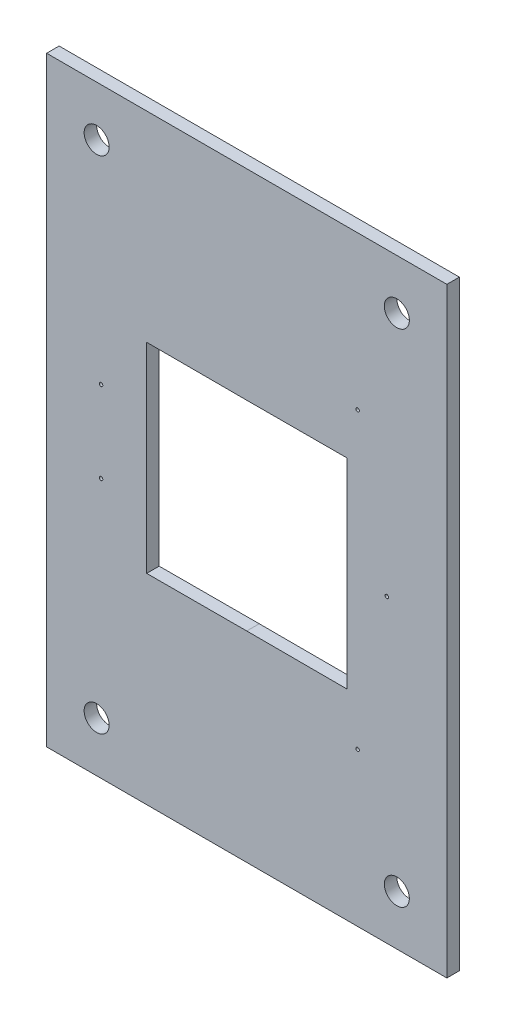
SolidWorks part; units mm, degrees
ref_plane "Front Plane" through (0, 0, 0) normal (0, 0, 1) x (1, 0, 0)
ref_plane "Top Plane" through (0, 0, 0) normal (0, 1, 0) x (1, 0, 0)
ref_plane "Right Plane" through (0, 0, 0) normal (1, 0, 0) x (0, 0, -1)
sketch "Sketch2" plane through (0, 0, 0) normal (0, 0, 1) x (1, 0, 0)
  line L0 (367.9685, -43.1374) -> (375.3903, -43.1374) construction
  line L1 (339.8232, 33.108) -> (339.8232, -119.3829) construction
  line L3 (365.2232, -43.1374) -> (365.2232, -17.7374) construction
  line L4 (365.2232, -17.7374) -> (339.8232, -17.7783)
  line L5 (365.2232, -17.7374) -> (365.2232, -68.5374)
  line L6 (314.4232, -17.7374) -> (339.8232, -17.7783)
  line L7 (314.4232, -17.7374) -> (314.4232, -68.5374)
  line L8 (365.2232, -68.5374) -> (339.8232, -68.4966)
  line L9 (314.4232, -68.5374) -> (339.8232, -68.4966)
  line L10 (390.6232, 33.108) -> (289.0232, 33.108)
  line L11 (289.0232, 33.108) -> (289.0232, -119.3829)
  line L12 (289.0232, -119.3829) -> (390.6232, -119.3829)
  line L13 (390.6232, 33.108) -> (390.6232, -119.3829)
  line L14 (289.0232, -43.1374) -> (302.835, -43.1374) construction
  line L15 (302.835, -43.1374) -> (302.835, -32.805) construction
  line L16 (302.835, -32.805) -> (367.9685, -5.8258) construction
  line L17 (367.9685, -5.8258) -> (367.9685, -43.1374) construction
  line L18 (368.6791, -6.2758) -> (368.6791, -5.8258) construction
  circle A0 centre (302.835, -32.805) radius 0.45
  circle A1 centre (367.9685, -5.8258) radius 0.45
  circle A2 centre (302.835, -53.4699) radius 0.45
  circle A3 centre (375.3903, -43.1374) radius 0.45
  circle A4 centre (367.9685, -80.449) radius 0.45
  point P28 (314.4232, -43.1374)
  dimension "D3" = 25.4
  dimension "D4" = 50.8
  dimension "D5" = 13.8118
extrude "Boss-Extrude1" add sketch "Sketch2" along normal blind 3.175
sketch "Sketch3" plane through (0, 0, 3.175) normal (0, 0, 1) x (1, 0, 0)
  line L0 (339.8232, 33.108) -> (339.8232, -119.3829) construction
  line L1 (390.6232, 33.108) -> (289.0232, 33.108) construction
  line L2 (289.0232, -119.3829) -> (390.6232, -119.3829) construction
  line L3 (289.0232, -43.1374) -> (390.6232, -43.1374) construction
  line L4 (289.0232, 33.108) -> (289.0232, -119.3829) construction
  line L5 (390.6232, -119.3829) -> (390.6232, 33.108) construction
  line L6 (390.6232, 33.108) -> (377.9232, 33.108) construction
  line L7 (377.9232, 33.108) -> (377.9232, 20.408) construction
  circle A0 centre (377.9232, 20.408) radius 3.175
  circle A1 centre (301.7232, 20.408) radius 3.175
  circle A2 centre (301.7232, -106.6829) radius 3.175
  circle A3 centre (377.9232, -106.6829) radius 3.175
  dimension "D1" = 12.7
  dimension "D2" = 12.7
extrude "Cut-Extrude1" cut sketch "Sketch3" against normal blind 10
